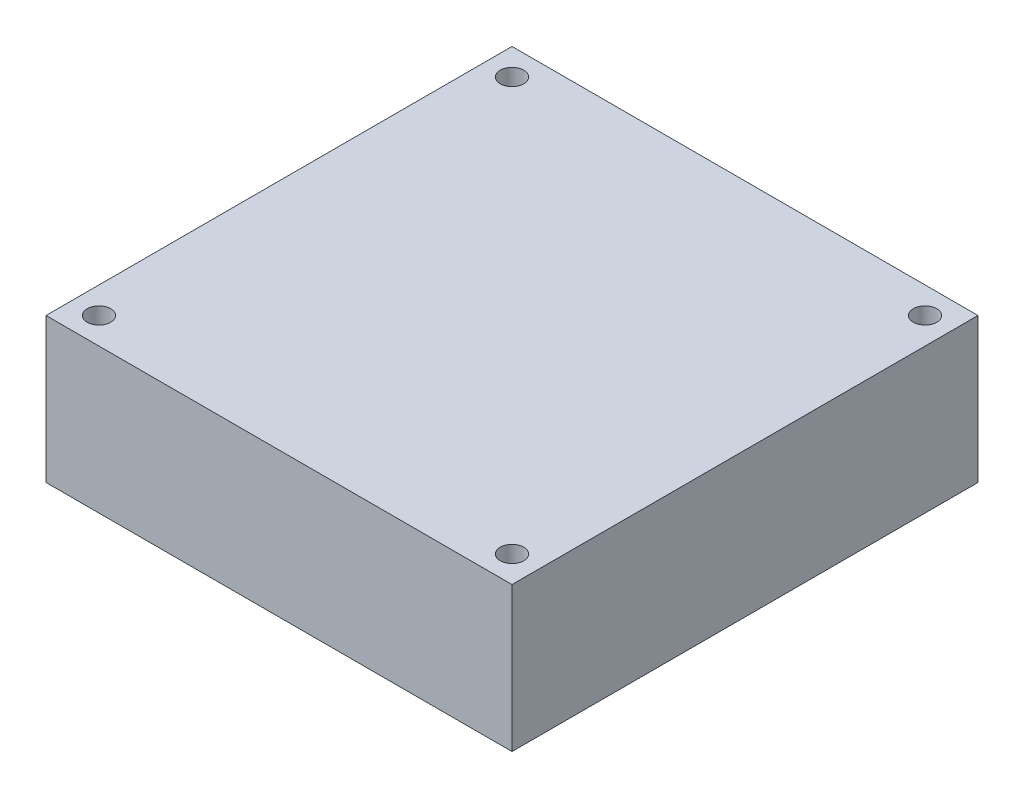
SolidWorks part; units mm, degrees
ref_plane "Front Plane" through (0, 0, 0) normal (0, 0, 1) x (1, 0, 0)
ref_plane "Top Plane" through (0, 0, 0) normal (0, 1, 0) x (1, 0, 0)
ref_plane "Right Plane" through (0, 0, 0) normal (1, 0, 0) x (0, 0, -1)
sketch "Sketch1" plane through (0, 0, 0) normal (0, 1, 0) x (1, 0, 0)
  line L1 (0, 0) -> (80.518, 0)
  line L2 (0, 0) -> (0, 80.518)
  line L3 (0, 80.518) -> (80.518, 80.518)
  line L4 (80.518, 0) -> (80.518, 80.518)
  dimension "D1" = 80.518
  dimension "D2" = 80.518
extrude "Boss-Extrude1" add sketch "Sketch1" along normal blind 24.9936
sketch "Sketch2" plane through (0, 24.9936, 0) normal (0, 1, 0) x (1, 0, 0)
  line L0 (75.946, 75.946) -> (4.572, 75.946) construction
  line L1 (80.518, 80.518) -> (0, 80.518) construction
  circle A0 centre (4.572, 75.946) radius 2.032
  circle A1 centre (75.946, 75.946) radius 2.032
  point P3 (40.259, 75.946)
  point P6 (40.259, 80.518)
  dimension "D3" = 4.064
  dimension "D4" = 4.064
  dimension "D1" = 71.374
  dimension "D2" = 4.572
extrude "Cut-Extrude1" cut sketch "Sketch2" against normal through all
ref_plane "Plane1" through (0, 0, -40.259) normal (0, 0, -1) x (-1, 0, 0)
mirror "Mirror1" about plane through (0, 0, -40.259) normal (0, 0, -1) of "Cut-Extrude1"
